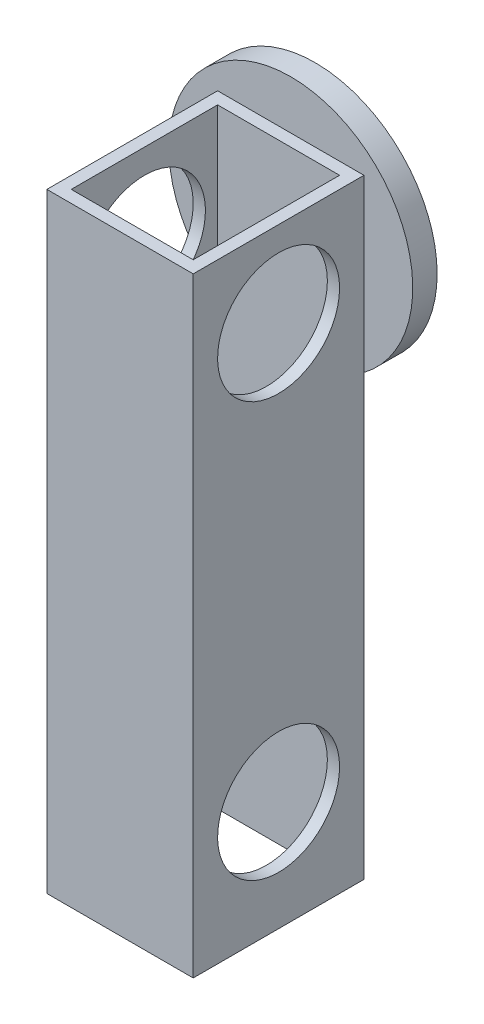
SolidWorks part; units mm, degrees
ref_plane "Front Plane" through (0, 0, 0) normal (0, 0, 1) x (1, 0, 0)
ref_plane "Top Plane" through (0, 0, 0) normal (0, 1, 0) x (1, 0, 0)
ref_plane "Right Plane" through (0, 0, 0) normal (1, 0, 0) x (0, 0, -1)
sketch "草图1" plane through (0, 0, 0) normal (0, 0, 1) x (1, 0, 0)
  circle A0 centre (0, 0) radius 50
  dimension "D1" = 100
extrude "凸台-拉伸1" add sketch "草图1" along normal blind 10
sketch "草图2" plane through (0, 0, 10) normal (0, 0, 1) x (1, 0, 0)
  point P0 (0, 0)
sketch "草图3" plane through (0, 0, 10) normal (0, 0, 1) x (1, 0, 0)
  line L1 (-30, 30) -> (30, 30)
  line L2 (-30, 30) -> (-30, -30)
  line L3 (-30, -30) -> (30, -30)
  line L4 (30, 30) -> (30, -30)
  line L5 (-30, 30) -> (30, -30) construction
  line L6 (-30, -30) -> (30, 30) construction
  point P0 (0, 0)
  dimension "D1" = 60
extrude "凸台-拉伸2" add sketch "草图3" along normal blind 70 contours L2 L1 L4 L3
sketch "草图4" plane through (0, -30, 0) normal (0, -1, 0) x (1, 0, 0)
  line L1 (-30, 80) -> (30, 80)
  line L2 (-30, 80) -> (-30, 10)
  line L3 (-30, 10) -> (30, 10)
  line L4 (30, 80) -> (30, 10)
extrude "凸台-拉伸3" add sketch "草图4" along normal blind 190
sketch "草图5" plane through (-30, 0, 0) normal (-1, 0, 0) x (0, 0, 1)
  line L0 (45, 48.964) -> (45, -245.9977) construction
  line L1 (80, 30) -> (10, 30) construction
  line L2 (80, -220) -> (10, -220) construction
  circle A0 centre (45, -5) radius 25
  circle A1 centre (45, -175) radius 25
  point P0 (45, 30)
  point P10 (0, 0)
  point P11 (0, 0)
  point P13 (0, 0)
  point P14 (45, -209.6602)
  point P15 (45, -245.9977)
  point P16 (45, -175)
  point P17 (0, 0)
  point P18 (45, -5)
  dimension "D1" = 50
  dimension "D2" = 35
  dimension "D3" = 45
sketch "草图6" plane through (0, -220, 0) normal (0, -1, 0) x (1, 0, 0)
  line L0 (30, 80) -> (-30, 80) construction
  line L1 (-25, 75) -> (25, 75)
  line L2 (-25, 75) -> (-25, 15)
  line L3 (-25, 15) -> (25, 15)
  line L4 (25, 75) -> (25, 15)
  line L5 (-30, 10) -> (30, 10) construction
  line L6 (30, 10) -> (30, 80) construction
  line L7 (-30, 70) -> (-30, 20) construction
  dimension "D1" = 5
  dimension "D2" = 5
  dimension "D3" = 5
  dimension "D4" = 5
extrude "切除-拉伸4" cut sketch "草图5" against normal blind 190
extrude "切除-拉伸5" cut sketch "草图6" against normal through all
